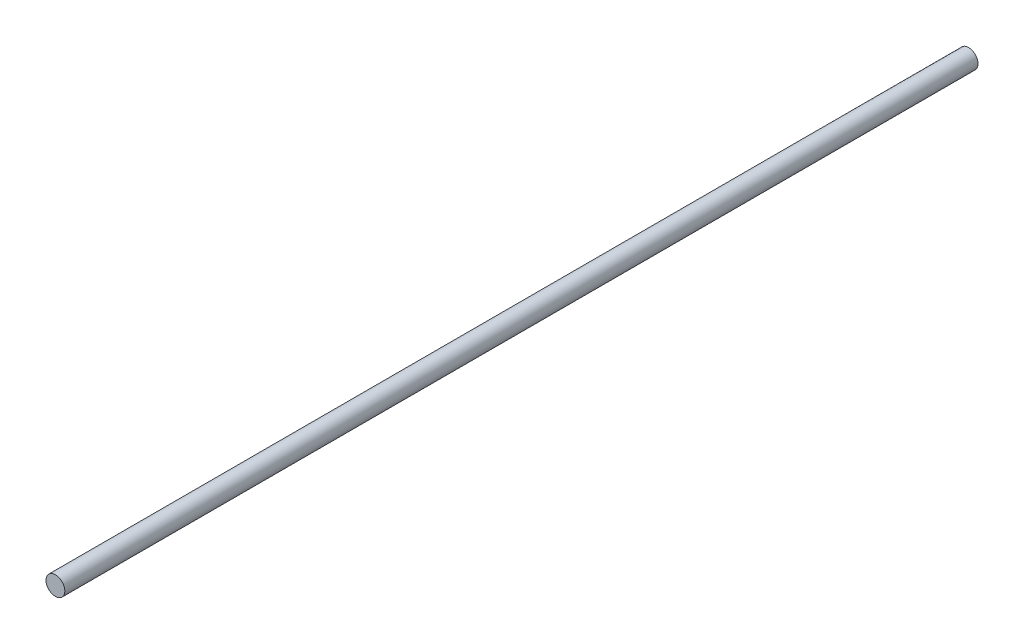
SolidWorks part; units mm, degrees
ref_plane "Ön Düzlem" through (0, 0, 0) normal (0, 0, 1) x (1, 0, 0)
ref_plane "Üst Düzlem" through (0, 0, 0) normal (0, 1, 0) x (1, 0, 0)
ref_plane "Sağ Düzlem" through (0, 0, 0) normal (1, 0, 0) x (0, 0, -1)
sketch "Çizim1" plane through (0, 0, 0) normal (0, 0, 1) x (1, 0, 0)
  circle A0 centre (0, 0) radius 6
  dimension "D1" = 12
extrude "Yükseklik-Ekstrüzyon1" add sketch "Çizim1" along normal blind 582
